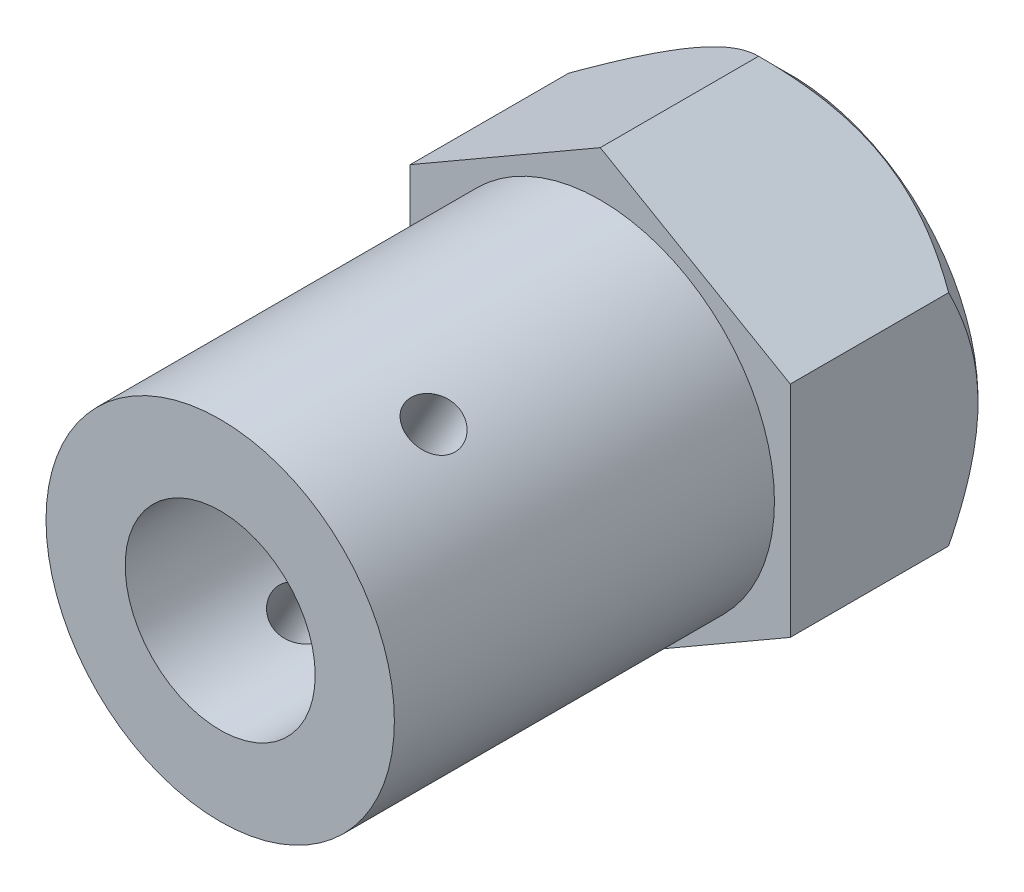
SolidWorks part; units mm, degrees
material "普通碳钢"
ref_plane "前视" through (0, 0, 0) normal (0, 0, 1) x (1, 0, 0)
ref_plane "上视" through (0, 0, 0) normal (0, 1, 0) x (1, 0, 0)
ref_plane "右视" through (0, 0, 0) normal (1, 0, 0) x (0, 0, -1)
sketch "草图1" plane through (0, 0, 0) normal (0, 0, 1) x (1, 0, 0)
  line L0 (0, 6.9282) -> (0, -6.9282) construction
  line L1 (-6, 3.4641) -> (6, -3.4641) construction
  line L2 (6, 3.4641) -> (-6, -3.4641) construction
  line L3 (-6, 3.4641) -> (0, 6.9282)
  line L4 (0, 6.9282) -> (6, 3.4641)
  line L5 (6, 3.4641) -> (6, -3.4641)
  line L6 (6, -3.4641) -> (0, -6.9282)
  line L7 (0, -6.9282) -> (-6, -3.4641)
  line L8 (-6, -3.4641) -> (-6, 3.4641)
  circle A0 centre (0, 0) radius 6.9282 construction
  dimension "D1" = 12
  dimension "D2" = 120
extrude "凸台-拉伸1" add sketch "草图1" along normal blind 6
sketch "草图2" plane through (0, 0, 6) normal (0, 0, 1) x (1, 0, 0)
  circle A0 centre (0, 0) radius 5.5
  dimension "D1" = 11
extrude "凸台-拉伸2" add sketch "草图2" along normal blind 12
hole_wizard "M3 螺纹孔1" positions "草图4" profile "草图3" tap size "M3" standard "GB"
sketch "草图4" plane through (0, 0, 0) normal (0, 0, -1) x (-1, 0, 0)
  point P0 (0, 0)
cosmetic thread "孔螺蚊线1" parameters "D1"=3.05, "D2"=3
sketch "草图3" plane through (0, 0, 0) normal (1, 0, 0) x (0, 1, 0)
  line L0 (0, 0) -> (0, 6.3011)
  line L1 (0, 6.3011) -> (1.25, 5.55)
  line L2 (1.25, 5.55) -> (1.25, 0)
  line L5 (1.25, 0) -> (0, 0)
  line L10 (0, 6.3011) -> (-1.25, 5.55) construction
  line L11 (0, -6.35) -> (0, 107.95) construction
  dimension "螺纹孔钻头直径" = 2.5
  dimension "螺纹孔钻头深度" = 5.55
  dimension "导头角度" = 118
ref_plane "基准面1" through (-2.75, -4.7631, 0) normal (-0.5, -0.866, 0) x (-0.866, 0.5, 0)
hole_wizard "M2 螺纹孔2" positions "草图8" profile "草图7" tap size "M2" standard "GB" end condition through all
sketch "草图8" plane through (-2.75, -4.7631, 0) normal (-0.5, -0.866, 0) x (-0.866, 0.5, 0)
  line L0 (-5.5, -18) -> (5.5, -18) construction
  line L1 (0, 0) -> (0, -18) construction
  point P2 (0, -14)
  dimension "D1" = 4
sketch "草图7" plane through (-2.75, -4.7631, 14) normal (0, 0, 1) x (0.866, -0.5, 0)
  line L0 (0, 0) -> (0, 14.5)
  line L1 (0, 14.5) -> (0.8, 14.5)
  line L2 (0.8, 14.5) -> (0.8, 0)
  line L5 (0.8, 0) -> (0, 0)
  line L11 (0, -6.35) -> (0, 107.95) construction
  dimension "通孔螺纹孔钻头直径" = 1.6
  dimension "通孔螺纹孔钻头深度" = 14.5
cosmetic thread "孔螺蚊线2" parameters "D2"=2
ref_plane "基准面2" through (0, 0, 0) normal (-0.5, -0.866, 0) x (-0.866, 0.5, 0)
sketch "草图10" plane through (0, 0, 0) normal (-0.5, -0.866, 0) x (-0.866, 0.5, 0)
  line L0 (0, 0) -> (0, -18) construction
  line L1 (-5.5, -18) -> (5.5, -18) construction
  line L2 (6.9282, 0) -> (5.9282, 0)
  line L3 (6.9282, 0) -> (3.4641, 0) construction
  line L4 (5.9282, 0) -> (6.9282, -1)
  line L5 (6.9282, -6) -> (6.9282, 0) construction
  line L6 (6.9282, -1) -> (6.9282, 0)
  dimension "D1" = 1
revolve "切除-旋转3" cut sketch "草图10" angle 360 about L0
sketch "草图11" plane through (0, 0, 18) normal (0, 0, 1) x (1, 0, 0)
  circle A0 centre (0, 0) radius 3
  dimension "D1" = 6
extrude "切除-拉伸1" cut sketch "草图11" against normal blind 10
